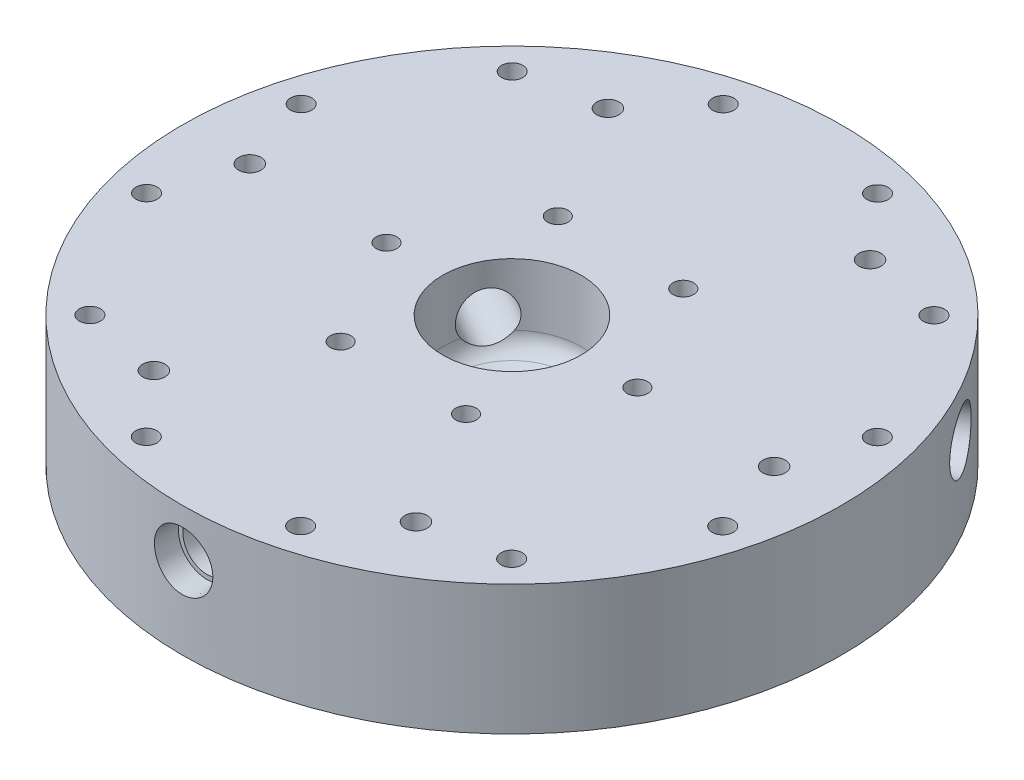
SolidWorks part; units mm, degrees
ref_plane "Front Plane" through (0, 0, 0) normal (0, 0, 1) x (1, 0, 0)
ref_plane "Top Plane" through (0, 0, 0) normal (0, 1, 0) x (1, 0, 0)
ref_plane "Right Plane" through (0, 0, 0) normal (1, 0, 0) x (0, 0, -1)
sketch "Sketch1" plane through (0, 0, 0) normal (0, 1, 0) x (1, 0, 0)
  circle A0 centre (0, 0) radius 76.2
  dimension "D1" = 152.4
extrude "Boss-Extrude1" add sketch "Sketch1" along normal blind 30
sketch "Sketch2" plane through (0, 0, 0) normal (0, 0, 1) x (1, 0, 0)
  line L0 (-5.9533, 0) -> (-5.9533, 4.1132)
  line L1 (-8.4533, 8.4434) -> (-13.5, 11.3571)
  line L2 (-16, 15.6872) -> (-16, 30)
  line L3 (76.2, 30) -> (-76.2, 30) construction
  line L4 (-16, 30) -> (0, 30)
  line L5 (0, 30) -> (0, 0)
  line L6 (0, 0) -> (-5.9533, 0)
  line L7 (-76.2, 0) -> (76.2, 0) construction
  arc A0 (-13.5, 11.3571) -> (-16, 15.6872) centre (-11, 15.6872) cw
  arc A1 (-5.9533, 4.1132) -> (-8.4533, 8.4434) centre (-10.9533, 4.1132) ccw
  point P15 (-5.9533, 7)
  dimension "D5" = 5
  dimension "D1" = 5.9533
  dimension "D2" = 7
  dimension "D3" = 16
  dimension "D4" = 30
revolve "Cut-Revolve1" cut sketch "Sketch2" angle 360 about L5
ref_plane "Plane1" through (0, 0, 80.54) normal (0, 0, 1) x (1, 0, 0)
hole_wizard "1/4 NPT Tapped Hole1" positions "Sketch4" profile "Sketch5" size "1/4" standard "ANSI Inch"
sketch "Sketch4" plane through (0, 0, 80.54) normal (0, 0, 1) x (1, 0, 0)
  point P0 (0, 18.9048)
sketch "Sketch5" plane through (0, 18.9048, 80.54) normal (1, 0, 0) x (0, -1, 0)
  line L0 (0, 0) -> (0, 83.8823)
  line L1 (5.5626, 80.54) -> (0, 83.8823)
  line L2 (-5.5626, 80.54) -> (0, 83.8823) construction
  line L3 (5.5626, 80.54) -> (5.5626, 10.02)
  line L4 (5.5626, 10.02) -> (6.5855, 10.02)
  line L5 (6.5855, 10.02) -> (6.858, 0.9208)
  line L6 (6.858, 0.9208) -> (7.7788, 0)
  line L7 (7.7788, 0) -> (0, 0)
  line L8 (0, -6.35) -> (0, 107.95) construction
  line L9 (-6.858, 0.9208) -> (-7.7788, 0) construction
  line L11 (-5.5626, 10.02) -> (-6.5855, 10.02) construction
  line L12 (-6.5855, 10.02) -> (-6.858, 0.9208) construction
  dimension "Tap Drill Dia." = 11.1252
  dimension "Tap Drill Depth" = 80.54
  dimension "Thread Dia." = 13.716
  dimension "Thread Angle" = 3.43
  dimension "Thread Depth" = 10.02
  dimension "C'Sink Dia." = 15.5575
  dimension "C'Sink Angle" = 90
  dimension "Drill Angle" = 118
pattern_circular "CirPattern1" count 3 over 360 about axis through (0, 0, 0) along (0, 1, 0) of "1/4 NPT Tapped Hole1"
hole_wizard "#10 (0.1935) Diameter Hole1" positions "Sketch6" profile "Sketch7" hole size "#10" standard "ANSI Inch" end condition through all
sketch "Sketch6" plane through (0, 30, 0) normal (0, 1, 0) x (1, 0, 0)
  arc A0 (-17.8145, 66.6607) -> (-17.8585, 66.6489) centre (0, 0) ccw
  point P0 (-17.8145, 66.6607)
  point P5 (-17.8145, 66.6607)
  point P14 (0, 0)
  point P15 (-17.8365, 66.6548)
  dimension "D1" = 69
sketch "Sketch7" plane through (-17.8145, 30, -66.6607) normal (1, 0, 0) x (0, 0, 1)
  line L0 (0, 0) -> (0, 30)
  line L1 (0, 30) -> (2.4574, 30)
  line L2 (2.4574, 30) -> (2.4574, 0)
  line L5 (2.4574, 0) -> (0, 0)
  line L11 (0, -6.35) -> (0, 107.95) construction
  dimension "Thru Hole Dia." = 4.9149
  dimension "Thru Hole Depth" = 30
pattern_circular "CirPattern2" count 12 over 360 about axis through (0, 0, 0) along (0, 1, 0) of "#10 (0.1935) Diameter Hole1"
sketch "Sketch12" plane through (0, 30, 0) normal (0, 1, 0) x (1, 0, 0)
  line L0 (0, 0) -> (0, 60.61)
  line L1 (0, 0) -> (30.305, 52.4898)
  circle A0 centre (0, 0) radius 60.61
  dimension "D1" = 121.22
  dimension "D2" = 30
hole_wizard "13/64 (0.20313) Diameter Hole3" positions "Sketch17" profile "Sketch19" hole size "13/64" standard "ANSI Inch"
sketch "Sketch17" plane through (0, 30, 0) normal (0, 1, 0) x (1, 0, 0)
  point P0 (30.305, 52.4898)
sketch "Sketch19" plane through (30.305, 30, -52.4898) normal (1, 0, 0) x (0, 0, 1)
  line L0 (0, 0) -> (0, 14.2501)
  line L1 (0, 14.2501) -> (2.5798, 12.7)
  line L2 (2.5798, 12.7) -> (2.5798, 0)
  line L5 (2.5798, 0) -> (0, 0)
  line L10 (0, 14.2501) -> (-2.5798, 12.7) construction
  line L11 (0, -6.35) -> (0, 107.95) construction
  dimension "Hole Dia." = 5.1595
  dimension "Hole Depth" = 12.7
  dimension "Drill Angle" = 118
pattern_circular "CirPattern3" count 6 over 360 about axis through (0, 0, 0) along (0, 1, 0) of "13/64 (0.20313) Diameter Hole3"
sketch "Sketch20" plane through (0, 0, 0) normal (0, -1, 0) x (-1, 0, 0)
  circle A0 centre (0, 0) radius 55.14
  dimension "D1" = 110.28
sketch "Sketch21" plane through (0, 0, 0) normal (0, 0, 1) x (1, 0, 0)
  line L0 (-76.2, 0) -> (76.2, 0) construction
  line L1 (60, 0) -> (65, 0)
  line L2 (60, 0) -> (60, 3)
  line L3 (60, 3) -> (65, 3)
  line L4 (65, 0) -> (65, 3)
  line L5 (0, 0) -> (0, -8.9782) construction
  dimension "D1" = 60
  dimension "D2" = 5
  dimension "D3" = 3
revolve "Cut-Revolve2" cut sketch "Sketch21" angle 360 about L5
hole_wizard "3/16 (0.1875) Diameter Hole1" positions "Sketch27" profile "Sketch28" hole size "3/16" standard "ANSI Inch"
sketch "Sketch27" plane through (0, 30, 0) normal (0, 1, 0) x (1, 0, 0)
  point P0 (29, 0)
  dimension "D1" = 29
sketch "Sketch28" plane through (29, 30, 0) normal (1, 0, 0) x (0, 0, 1)
  line L0 (0, 0) -> (0, 13.4308)
  line L1 (0, 13.4308) -> (2.3812, 12)
  line L2 (2.3812, 12) -> (2.3812, 0)
  line L5 (2.3812, 0) -> (0, 0)
  line L10 (0, 13.4308) -> (-2.3813, 12) construction
  line L11 (0, -6.35) -> (0, 107.95) construction
  dimension "Hole Dia." = 4.7625
  dimension "Hole Depth" = 12
  dimension "Drill Angle" = 118
pattern_circular "CirPattern4" count 6 over 360 about axis through (0, 0, 0) along (0, 1, 0) of "3/16 (0.1875) Diameter Hole1"
sketch "Sketch29" plane through (0, 0, 0) normal (0, -1, 0) x (-1, 0, 0)
  circle A0 centre (0, 0) radius 55.14
  circle A1 centre (0, 0) radius 5.9533
  dimension "D1" = 110.28
extrude "Boss-Extrude2" add sketch "Sketch29" along normal blind 2
